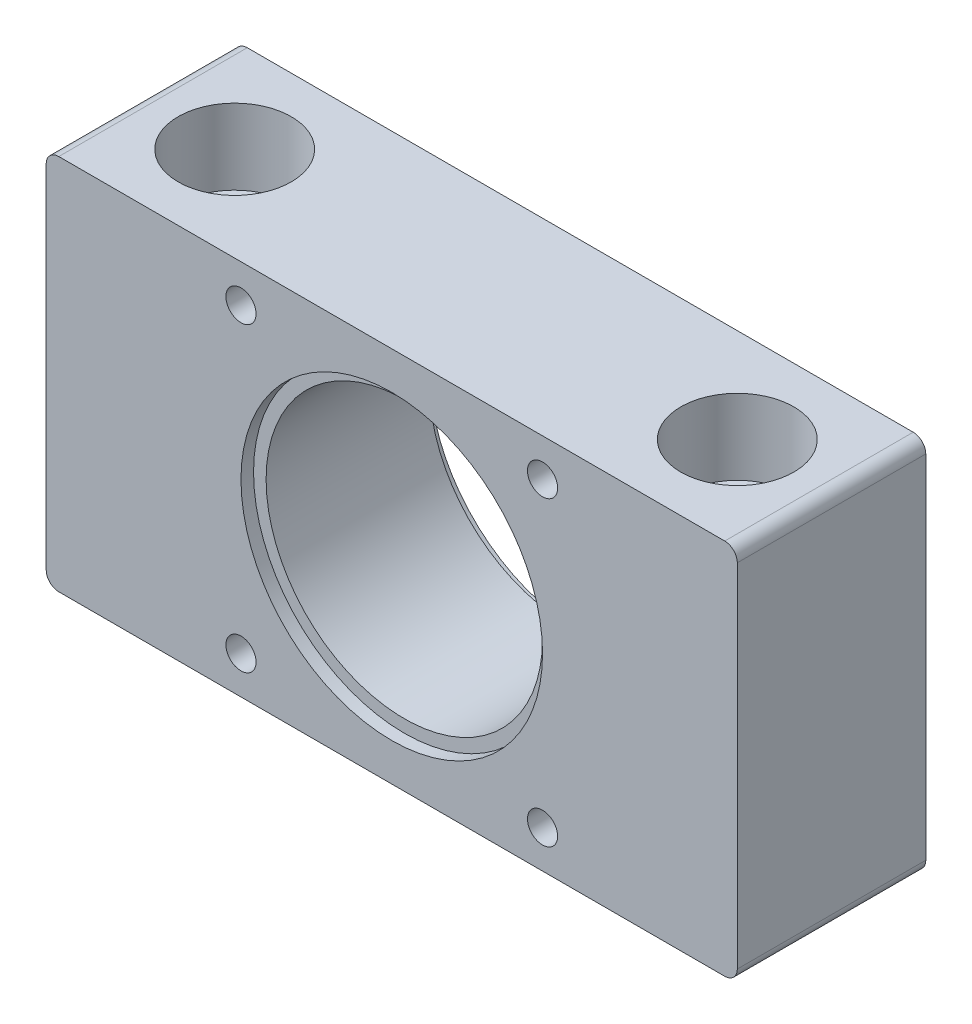
SolidWorks part; units mm, degrees
material "6061 合金"
ref_plane "前视基准面" through (0, 0, 0) normal (0, 0, 1) x (1, 0, 0)
ref_plane "上视基准面" through (0, 0, 0) normal (0, 1, 0) x (1, 0, 0)
ref_plane "右视基准面" through (0, 0, 0) normal (1, 0, 0) x (0, 0, -1)
sketch "草图1" plane through (0, 0, 0) normal (0, 0, 1) x (1, 0, 0)
  line L1 (-27.5, 15) -> (27.5, 15)
  line L2 (-27.5, 15) -> (-27.5, -15)
  line L3 (-27.5, -15) -> (27.5, -15)
  line L4 (27.5, 15) -> (27.5, -15)
  line L5 (0, -15) -> (0, 15) construction
  line L6 (-27.5, 0) -> (27.5, 0) construction
  circle A0 centre (0, 0) radius 11
  point P44 (0, 0)
  dimension "D1" = 15
  dimension "D2" = 22
  dimension "D3" = 55
  dimension "D4" = 30
extrude "凸台-拉伸1" add sketch "草图1" along normal blind 15
sketch "草图2" plane through (0, 15, 0) normal (0, 1, 0) x (1, 0, 0)
  line L0 (0, 0) -> (0, -15) construction
  line L1 (27.5, -15) -> (-27.5, -15) construction
  line L2 (-27.5, -7.5) -> (27.5, -7.5) construction
  line L3 (-27.5, -15) -> (-27.5, 0) construction
  line L4 (27.5, -15) -> (27.5, 0) construction
  circle A0 centre (-20, -7.5) radius 2.55
  circle A1 centre (20, -7.5) radius 2.55
  dimension "D1" = 5.1
  dimension "D2" = 40
extrude "切除-拉伸1" cut sketch "草图2" against normal through all
sketch "草图4" plane through (0, 0, 0) normal (0, 0, -1) x (-1, 0, 0)
  circle A0 centre (0, 0) radius 12
  circle A1 centre (0, 0) radius 11 construction
  dimension "D1" = 1
extrude "切除-拉伸3" cut sketch "草图4" against normal blind 1
sketch "草图5" plane through (0, 0, 15) normal (0, 0, 1) x (1, 0, 0)
  circle A0 centre (0, 0) radius 12
  circle A1 centre (0, 0) radius 11 construction
  dimension "D1" = 1
extrude "切除-拉伸4" cut sketch "草图5" against normal blind 1
sketch "草图6" plane through (0, 0, 15) normal (0, 0, 1) x (1, 0, 0)
  line L1 (-12, 12) -> (12, 12) construction
  line L2 (-12, 12) -> (-12, -12) construction
  line L3 (-12, -12) -> (12, -12) construction
  line L4 (12, 12) -> (12, -12) construction
  line L5 (0, -12) -> (0, 12) construction
  line L6 (-12, 0) -> (12, 0) construction
  circle A1 centre (12, 12) radius 1.2
  circle A2 centre (-12, 12) radius 1.2
  circle A3 centre (-12, -12) radius 1.2
  circle A4 centre (12, -12) radius 1.2
  point P116 (0, 0)
  dimension "D3" = 2.4
  dimension "D1" = 24
  dimension "D2" = 24
extrude "切除-拉伸5" cut sketch "草图6" against normal through all
cosmetic thread "装饰螺纹线1" parameters "D2"=3
cosmetic thread "装饰螺纹线2" parameters "D2"=3
cosmetic thread "装饰螺纹线3" parameters "D2"=3
cosmetic thread "装饰螺纹线4" parameters "D2"=3
fillet "圆角2" radius 1 4 edges at (-27.5, 15, 7.5) (27.5, -15, 7.5) (-27.5, -15, 7.5) (27.5, 15, 7.5)
sketch "草图7" plane through (0, 15, 0) normal (0, 1, 0) x (1, 0, 0)
  circle A0 centre (-20, -7.5) radius 4.5
  circle A1 centre (20, -7.5) radius 4.5
  dimension "D1" = 9
extrude "切除-拉伸6" cut sketch "草图7" against normal blind 6
